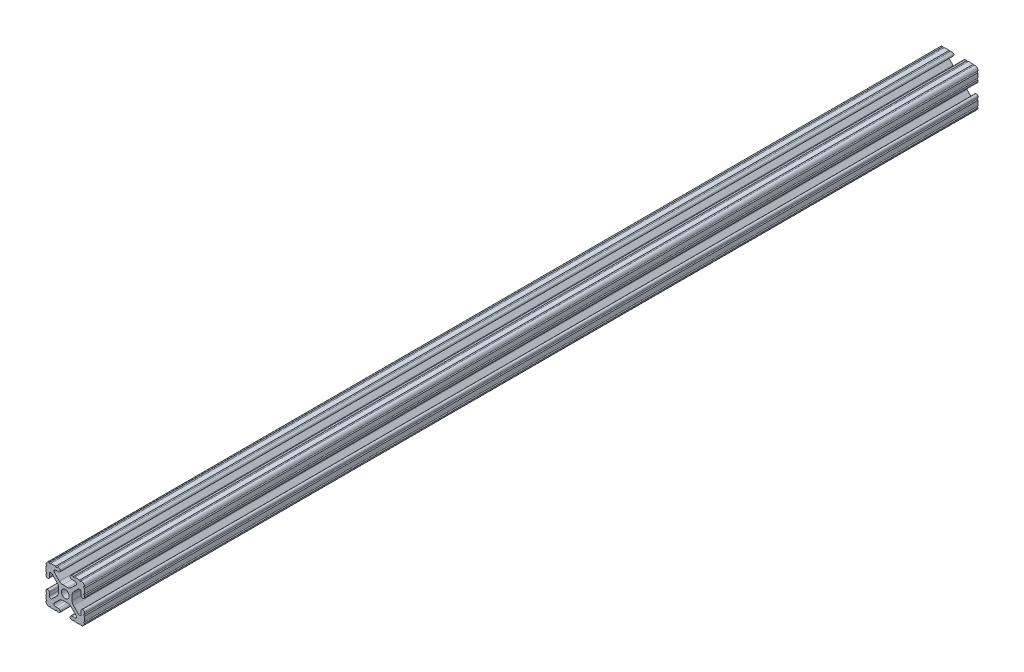
SolidWorks part; units mm, degrees
ref_plane "Front Plane" through (0, 0, 0) normal (0, 0, 1) x (1, 0, 0)
ref_plane "Top Plane" through (0, 0, 0) normal (0, 1, 0) x (1, 0, 0)
ref_plane "Right Plane" through (0, 0, 0) normal (1, 0, 0) x (0, 0, -1)
sketch "Sketch1" plane through (0, 0, 0) normal (0, 0, 1) x (1, 0, 0)
  line L0 (-12.7, -6.3331) -> (-12.7, -9.5504)
  line L1 (-9.5504, -12.7) -> (-6.3331, -12.7)
  line L2 (-5.3171, -12.7) -> (-4.3434, -12.7)
  line L3 (-4.3434, -10.4902) -> (-6.4748, -10.4902)
  line L4 (-7.1932, -8.7558) -> (-3.8632, -5.4257)
  line L5 (-1.6181, -4.4958) -> (1.6181, -4.4958)
  line L6 (3.8632, -5.4257) -> (7.1932, -8.7558)
  line L7 (6.4748, -10.4902) -> (4.3434, -10.4902)
  line L8 (4.3434, -12.7) -> (5.3171, -12.7)
  line L9 (6.3331, -12.7) -> (9.5504, -12.7)
  line L10 (12.7, -9.5504) -> (12.7, -6.3331)
  line L11 (12.7, -5.3171) -> (12.7, -4.3434)
  line L12 (10.4902, -4.3434) -> (10.4902, -6.4748)
  line L13 (8.7558, -7.1932) -> (5.4257, -3.8632)
  line L14 (4.4958, -1.6181) -> (4.4958, 1.6181)
  line L15 (5.4257, 3.8632) -> (8.7558, 7.1932)
  line L16 (10.4902, 6.4748) -> (10.4902, 4.3434)
  line L17 (12.7, 4.3434) -> (12.7, 5.3171)
  line L18 (12.7, 6.3331) -> (12.7, 9.5504)
  line L19 (9.5504, 12.7) -> (6.3331, 12.7)
  line L20 (5.3171, 12.7) -> (4.3434, 12.7)
  line L21 (4.3434, 10.4902) -> (6.4748, 10.4902)
  line L22 (7.1932, 8.7558) -> (3.8632, 5.4257)
  line L23 (1.6181, 4.4958) -> (-1.6181, 4.4958)
  line L24 (-3.8632, 5.4257) -> (-7.1932, 8.7558)
  line L25 (-6.4748, 10.4902) -> (-4.3434, 10.4902)
  line L26 (-4.3434, 12.7) -> (-5.3171, 12.7)
  line L27 (-6.3331, 12.7) -> (-9.5504, 12.7)
  line L28 (-12.7, 9.5504) -> (-12.7, 6.3331)
  line L29 (-12.7, 5.3171) -> (-12.7, 4.3434)
  line L30 (-10.4902, 4.3434) -> (-10.4902, 6.4748)
  line L31 (-8.7558, 7.1932) -> (-5.4257, 3.8632)
  line L32 (-4.4958, 1.6181) -> (-4.4958, -1.6181)
  line L33 (-5.4257, -3.8632) -> (-8.7558, -7.1932)
  line L34 (-10.4902, -6.4748) -> (-10.4902, -4.3434)
  line L35 (-12.7, -4.3434) -> (-12.7, -5.3171)
  circle A0 centre (0, 0) radius 2.6035
  arc A1 (-12.7, -5.3171) -> (-12.7, -6.3331) centre (-12.7, -5.8251) cw
  arc A2 (-12.7, -9.5504) -> (-12.6998, -10.5664) centre (-12.7, -10.0584) cw
  arc A3 (-12.6998, -10.5664) -> (-10.5664, -12.6998) centre (-10.5918, -10.5918) ccw
  arc A4 (-10.5664, -12.6998) -> (-9.5504, -12.7) centre (-10.0584, -12.7) cw
  arc A5 (-6.3331, -12.7) -> (-5.3171, -12.7) centre (-5.8251, -12.7) cw
  arc A6 (-4.3434, -12.7) -> (-4.3434, -10.4902) centre (-4.3434, -11.5951) ccw
  arc A7 (-6.4748, -10.4902) -> (-7.1932, -8.7558) centre (-6.4748, -9.4742) cw
  arc A8 (-3.8632, -5.4257) -> (-1.6181, -4.4958) centre (-1.6181, -7.6708) cw
  arc A9 (1.6181, -4.4958) -> (3.8632, -5.4257) centre (1.6181, -7.6708) cw
  arc A10 (7.1932, -8.7558) -> (6.4748, -10.4902) centre (6.4748, -9.4742) cw
  arc A11 (4.3434, -10.4902) -> (4.3434, -12.7) centre (4.3434, -11.5951) ccw
  arc A12 (5.3171, -12.7) -> (6.3331, -12.7) centre (5.8251, -12.7) cw
  arc A13 (9.5504, -12.7) -> (10.5664, -12.6998) centre (10.0584, -12.7) cw
  arc A14 (10.5664, -12.6998) -> (12.6998, -10.5664) centre (10.5918, -10.5918) ccw
  arc A15 (12.6998, -10.5664) -> (12.7, -9.5504) centre (12.7, -10.0584) cw
  arc A16 (12.7, -6.3331) -> (12.7, -5.3171) centre (12.7, -5.8251) cw
  arc A17 (12.7, -4.3434) -> (10.4902, -4.3434) centre (11.5951, -4.3434) ccw
  arc A18 (10.4902, -6.4748) -> (8.7558, -7.1932) centre (9.4742, -6.4748) cw
  arc A19 (5.4257, -3.8632) -> (4.4958, -1.6181) centre (7.6708, -1.6181) cw
  arc A20 (4.4958, 1.6181) -> (5.4257, 3.8632) centre (7.6708, 1.6181) cw
  arc A21 (8.7558, 7.1932) -> (10.4902, 6.4748) centre (9.4742, 6.4748) cw
  arc A22 (10.4902, 4.3434) -> (12.7, 4.3434) centre (11.5951, 4.3434) ccw
  arc A23 (12.7, 5.3171) -> (12.7, 6.3331) centre (12.7, 5.8251) cw
  arc A24 (12.7, 9.5504) -> (12.6998, 10.5664) centre (12.7, 10.0584) cw
  arc A25 (12.6998, 10.5664) -> (10.5664, 12.6998) centre (10.5918, 10.5918) ccw
  arc A26 (10.5664, 12.6998) -> (9.5504, 12.7) centre (10.0584, 12.7) cw
  arc A27 (6.3331, 12.7) -> (5.3171, 12.7) centre (5.8251, 12.7) cw
  arc A28 (4.3434, 12.7) -> (4.3434, 10.4902) centre (4.3434, 11.5951) ccw
  arc A29 (6.4748, 10.4902) -> (7.1932, 8.7558) centre (6.4748, 9.4742) cw
  arc A30 (3.8632, 5.4257) -> (1.6181, 4.4958) centre (1.6181, 7.6708) cw
  arc A31 (-1.6181, 4.4958) -> (-3.8632, 5.4257) centre (-1.6181, 7.6708) cw
  arc A32 (-7.1932, 8.7558) -> (-6.4748, 10.4902) centre (-6.4748, 9.4742) cw
  arc A33 (-4.3434, 10.4902) -> (-4.3434, 12.7) centre (-4.3434, 11.5951) ccw
  arc A34 (-5.3171, 12.7) -> (-6.3331, 12.7) centre (-5.8251, 12.7) cw
  arc A35 (-9.5504, 12.7) -> (-10.5664, 12.6998) centre (-10.0584, 12.7) cw
  arc A36 (-10.5664, 12.6998) -> (-12.6998, 10.5664) centre (-10.5918, 10.5918) ccw
  arc A37 (-12.6998, 10.5664) -> (-12.7, 9.5504) centre (-12.7, 10.0584) cw
  arc A38 (-12.7, 6.3331) -> (-12.7, 5.3171) centre (-12.7, 5.8251) cw
  arc A39 (-12.7, 4.3434) -> (-10.4902, 4.3434) centre (-11.5951, 4.3434) ccw
  arc A40 (-10.4902, 6.4748) -> (-8.7558, 7.1932) centre (-9.4742, 6.4748) cw
  arc A41 (-5.4257, 3.8632) -> (-4.4958, 1.6181) centre (-7.6708, 1.6181) cw
  arc A42 (-4.4958, -1.6181) -> (-5.4257, -3.8632) centre (-7.6708, -1.6181) cw
  arc A43 (-8.7558, -7.1932) -> (-10.4902, -6.4748) centre (-9.4742, -6.4748) cw
  arc A44 (-10.4902, -4.3434) -> (-12.7, -4.3434) centre (-11.5951, -4.3434) ccw
extrude "Boss-Extrude1" add sketch "Sketch1" against normal blind 590.55
